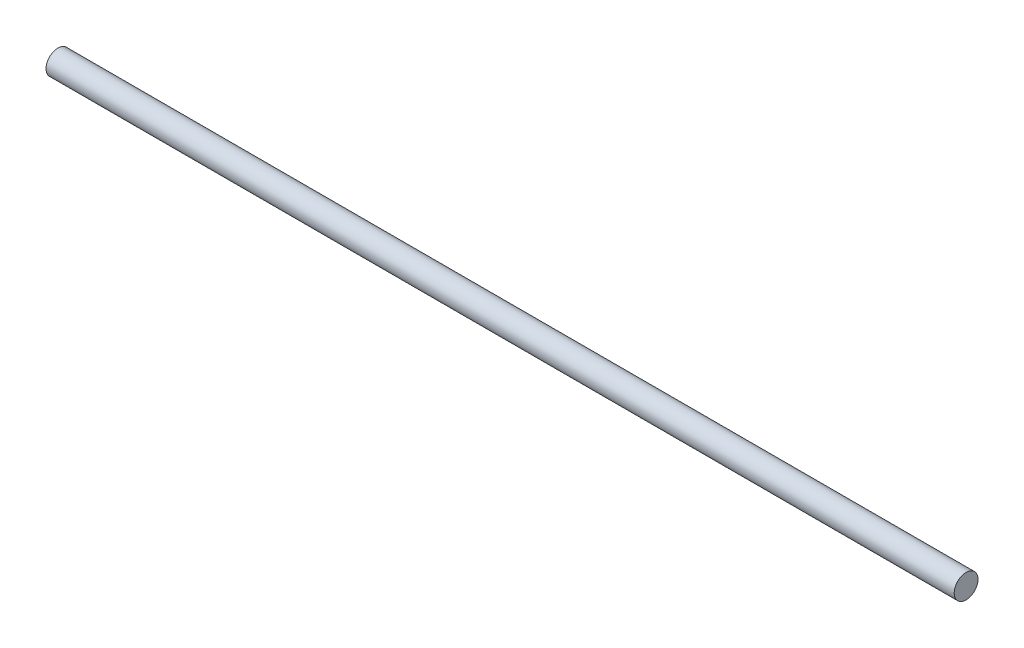
SolidWorks part; units mm, degrees
ref_plane "Front Plane" through (0, 0, 0) normal (0, 0, 1) x (1, 0, 0)
ref_plane "Top Plane" through (0, 0, 0) normal (0, 1, 0) x (1, 0, 0)
ref_plane "Right Plane" through (0, 0, 0) normal (1, 0, 0) x (0, 0, -1)
sketch "Sketch1" plane through (0, 0, 0) normal (1, 0, 0) x (0, 0, -1)
  circle A0 centre (0, 0) radius 8
extrude "Boss-Extrude1" add sketch "Sketch1" along normal mid plane 609.6
